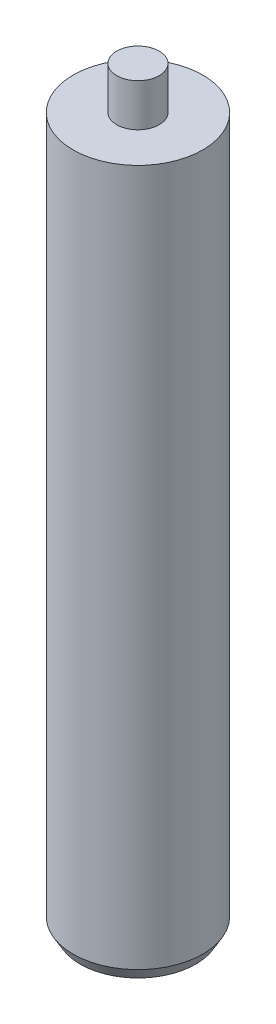
SolidWorks part; units mm, degrees
ref_plane "Front Plane" through (0, 0, 0) normal (0, 0, 1) x (1, 0, 0)
ref_plane "Top Plane" through (0, 0, 0) normal (0, 1, 0) x (1, 0, 0)
ref_plane "Right Plane" through (0, 0, 0) normal (1, 0, 0) x (0, 0, -1)
sketch "Sketch2" plane through (0, 0, 0) normal (0, 1, 0) x (1, 0, 0)
  circle A0 centre (0, 0) radius 9.15
  dimension "D1" = 18.3
extrude "Boss-Extrude1" add sketch "Sketch2" along normal blind 100
sketch "Sketch3" plane through (0, 100, 0) normal (0, 1, 0) x (1, 0, 0)
  circle A0 centre (0, 0) radius 3
extrude "Boss-Extrude2" add sketch "Sketch3" along normal blind 6
chamfer "Chamfer1" distance 1 angle 60 1 edges at (0, 0, 9.15)
